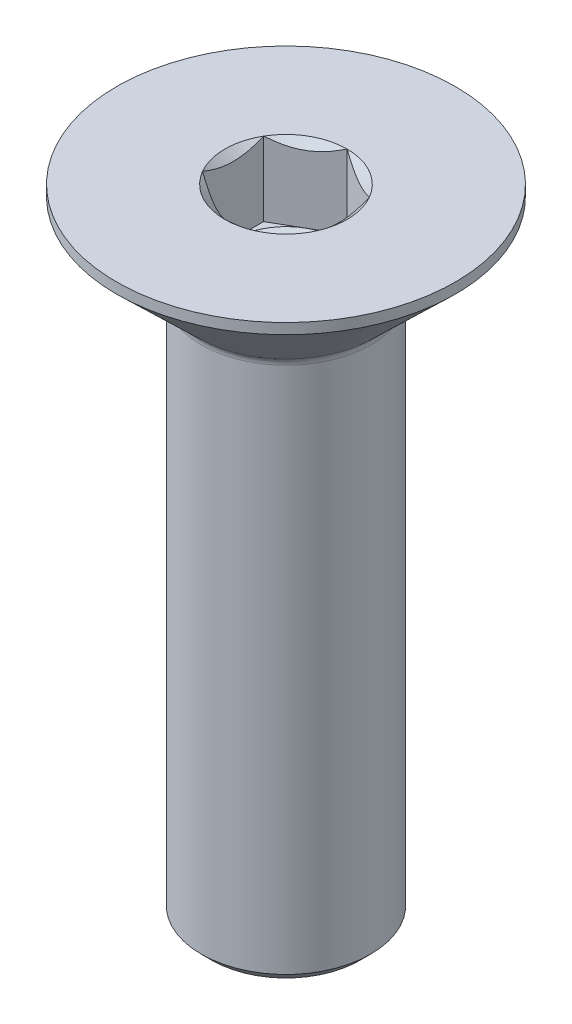
SolidWorks part; units mm, degrees
material "Galvanized Steel"
ref_plane "Front Plane" through (0, 0, 0) normal (0, 0, 1) x (1, 0, 0)
ref_plane "Top Plane" through (0, 0, 0) normal (0, 1, 0) x (1, 0, 0)
ref_plane "Right Plane" through (0, 0, 0) normal (1, 0, 0) x (0, 0, -1)
sketch "Sketch1" plane through (0, 0, 0) normal (0, 0, 1) x (1, 0, 0)
  line L0 (0, 0) -> (-8, 0)
  line L1 (-8, 0) -> (-8, -0.5)
  line L2 (-8, -0.5) -> (-4, -4.3628)
  line L3 (-4, -4.3628) -> (-4, -30)
  line L4 (-4, -30) -> (0, -30)
  line L5 (0, -30) -> (0, 0)
  line L6 (0, 0) -> (0, 13.0978) construction
  dimension "D1" = 46
  dimension "D2" = 8
  dimension "D3" = 16
  dimension "D4" = 0.5
  dimension "D5" = 30
revolve "Revolve1" add sketch "Sketch1" angle 360 about L6
sketch "Sketch2" plane through (0, 0, 0) normal (0, 1, 0) x (1, 0, 0)
  line L1 (0, 2.8868) -> (-2.5, 1.4434)
  line L2 (-2.5, 1.4434) -> (-2.5, -1.4434)
  line L3 (-2.5, -1.4434) -> (0, -2.8868)
  line L4 (0, -2.8868) -> (2.5, -1.4434)
  line L5 (2.5, -1.4434) -> (2.5, 1.4434)
  line L6 (2.5, 1.4434) -> (0, 2.8868)
  circle A0 centre (0, 0) radius 2.5 construction
  dimension "D1" = 5
extrude "Cut-Extrude1" cut sketch "Sketch2" against normal blind 3.5
sketch "Sketch3" plane through (0, 0, 0) normal (0, 0, 1) x (1, 0, 0)
  line L1 (8, 0) -> (-8, 0) construction
  line L2 (-2.5, -0.3231) -> (-2.885, 0)
  line L3 (-2.5, -0.3231) -> (-2.5, -3.5)
  line L4 (-2.5, -3.5) -> (0, -3.5) construction
  line L5 (-2.5, -3.5) -> (0, -4.4099)
  line L6 (0, -4.4099) -> (0, 0)
  line L7 (-2.885, 0) -> (0, 0)
  line L8 (0, -4.4099) -> (0, -30) construction
  line L9 (-4, -30) -> (4, -30) construction
  line L10 (-2.5, -3.5) -> (-2.5, 0) construction
  dimension "D1" = 40
  dimension "D2" = 5.77
  dimension "D3" = 20
revolve "Cut-Revolve1" cut sketch "Sketch3" angle 360 about L8
fillet "Fillet1" radius 0.5 1 edges at (0, -4.3628, -4)
chamfer "Chamfer1" distance 0.5 angle 45 1 edges at (0, -30, -4)
cosmetic thread "Cosmetic Thread2" parameters "D2"=6.619
